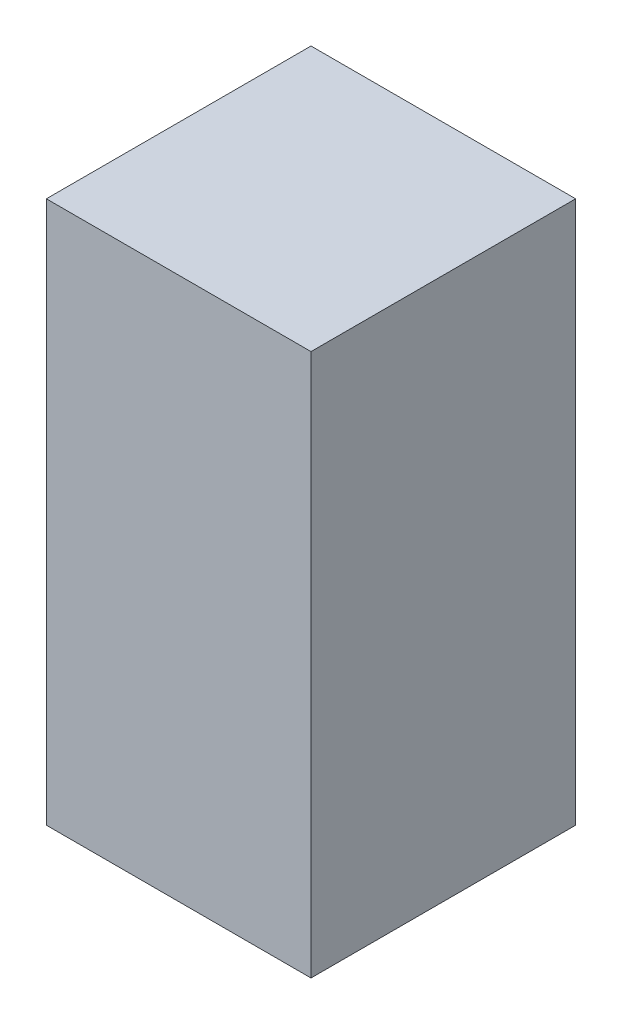
SolidWorks part; units mm, degrees
ref_plane "Front Plane" through (0, 0, 0) normal (0, 0, 1) x (1, 0, 0)
ref_plane "Top Plane" through (0, 0, 0) normal (0, 1, 0) x (1, 0, 0)
ref_plane "Right Plane" through (0, 0, 0) normal (1, 0, 0) x (0, 0, -1)
sketch "Sketch1" plane through (0, 0, 0) normal (1, 0, 0) x (0, 0, -1)
  line L1 (-1, 2.05) -> (1, 2.05)
  line L2 (-1, 2.05) -> (-1, -2.05)
  line L3 (-1, -2.05) -> (1, -2.05)
  line L4 (1, 2.05) -> (1, -2.05)
  line L5 (-1, 2.05) -> (1, -2.05) construction
  line L6 (-1, -2.05) -> (1, 2.05) construction
  point P0 (0, 0)
  dimension "D1" = 2
  dimension "D2" = 4.1
extrude "Boss-Extrude1" add sketch "Sketch1" along normal blind 2
